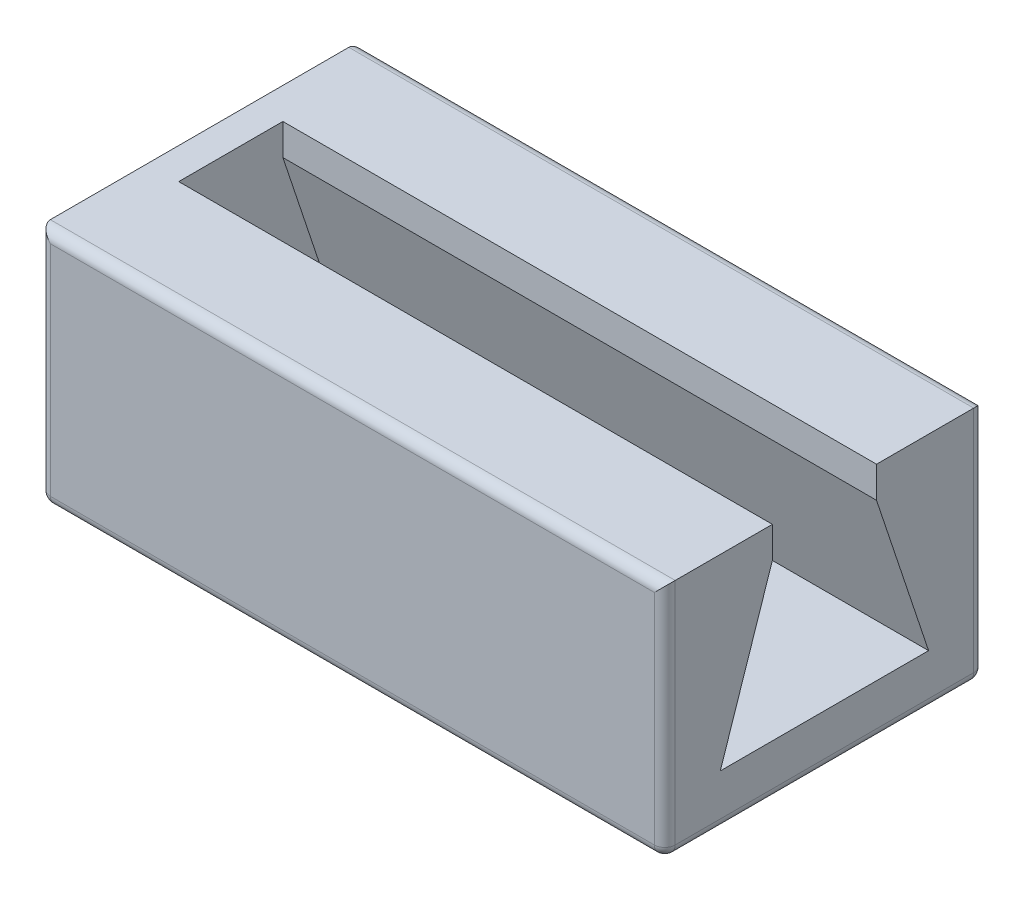
SolidWorks part; units mm, degrees
ref_plane "Front Plane" through (0, 0, 0) normal (0, 0, 1) x (1, 0, 0)
ref_plane "Top Plane" through (0, 0, 0) normal (0, 1, 0) x (1, 0, 0)
ref_plane "Right Plane" through (0, 0, 0) normal (1, 0, 0) x (0, 0, -1)
sketch "Sketch2" plane through (0, 0, 0) normal (1, 0, 0) x (0, 0, -1)
  line L0 (0, 0) -> (0, 23)
  line L1 (0, 23) -> (10.33, 23)
  line L2 (10.33, 23) -> (10.33, 20)
  line L3 (10.33, 20) -> (5.33, 4.9957)
  line L4 (5.33, 4.9957) -> (25.33, 4.9957)
  line L5 (25.33, 4.9957) -> (20.33, 20)
  line L6 (20.33, 20) -> (20.33, 23)
  line L7 (20.33, 23) -> (30.66, 23)
  line L8 (30.66, 23) -> (30.66, 0)
  line L9 (30.66, 0) -> (0, 0)
  dimension "D1" = 23
  dimension "D2" = 23
  dimension "D3" = 71.57
  dimension "D4" = 71.57
  dimension "D5" = 5.33
  dimension "D6" = 5.33
  dimension "D7" = 20
  dimension "D8" = 20
  dimension "D9" = 5
  dimension "D10" = 20
extrude "Boss-Extrude1" add sketch "Sketch2" along normal blind 60
fillet "Fillet1" radius 1 10 edges at (30, 0, -30.66) (60, 11.5, -30.66) (30, 23, -30.66) (0, 11.5, -30.66) (30, 23, 0) (60, 11.5, 0) (30, 0, 0) (0, 11.5, 0) (0, 0, -15.33) (60, 0, -15.33)
sketch "Sketch3" plane through (0, 0, 0) normal (-1, 0, 0) x (0, 0, 1)
  line L0 (-20.33, 23) -> (-10.33, 23)
  line L1 (-10.33, 23) -> (-10.33, 20)
  line L2 (-10.33, 20) -> (-5.33, 4.9957)
  line L3 (-5.33, 4.9957) -> (-25.33, 4.9957)
  line L4 (-25.33, 4.9957) -> (-20.33, 20)
  line L5 (-20.33, 20) -> (-20.33, 23)
extrude "Boss-Extrude2" add sketch "Sketch3" against normal blind 3
